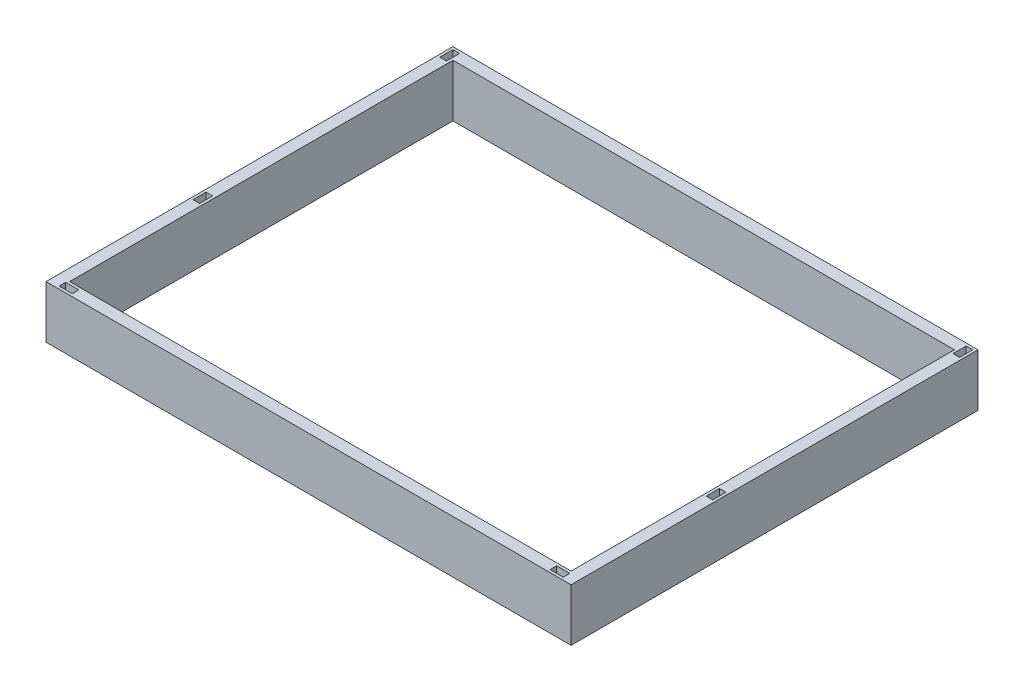
SolidWorks part; units mm, degrees
material "ABS"
ref_plane "Front Plane" through (0, 0, 0) normal (0, 0, 1) x (1, 0, 0)
ref_plane "Top Plane" through (0, 0, 0) normal (0, 1, 0) x (1, 0, 0)
ref_plane "Right Plane" through (0, 0, 0) normal (1, 0, 0) x (0, 0, -1)
sketch "Sketch1" plane through (0, 0, 0) normal (0, 1, 0) x (1, 0, 0)
  line L1 (100, 77.5) -> (-100, 77.5)
  line L2 (100, 77.5) -> (100, -77.5)
  line L3 (100, -77.5) -> (-100, -77.5)
  line L4 (-100, 77.5) -> (-100, -77.5)
  line L5 (100, 77.5) -> (-100, -77.5) construction
  line L6 (100, -77.5) -> (-100, 77.5) construction
  line L15 (95.5, 73) -> (-95.5, 73)
  line L16 (95.5, 73) -> (95.5, -73)
  line L21 (95.5, -73) -> (-95.5, -73)
  line L22 (-95.5, 73) -> (-95.5, -73)
  line L35 (96, -76.5) -> (91, -76.5)
  line L36 (96, -76.5) -> (96, -74)
  line L37 (96, -74) -> (91, -74)
  line L38 (91, -76.5) -> (91, -74)
  line L39 (96, -76.5) -> (91, -74) construction
  line L40 (96, -74) -> (91, -76.5) construction
  line L47 (-96, -76.5) -> (-91, -76.5)
  line L48 (-96, -76.5) -> (-96, -74)
  line L49 (-96, -74) -> (-91, -74)
  line L50 (-91, -76.5) -> (-91, -74)
  line L51 (-96, -76.5) -> (-91, -74) construction
  line L52 (-96, -74) -> (-91, -76.5) construction
  line L65 (99, -17.5) -> (96.5, -17.5)
  line L66 (99, -17.5) -> (99, -22.5)
  line L67 (99, -22.5) -> (96.5, -22.5)
  line L68 (96.5, -17.5) -> (96.5, -22.5)
  line L69 (99, -17.5) -> (96.5, -22.5) construction
  line L70 (99, -22.5) -> (96.5, -17.5) construction
  line L71 (99, 76.5) -> (96.5, 76.5)
  line L72 (99, 76.5) -> (99, 71.5)
  line L73 (99, 71.5) -> (96.5, 71.5)
  line L74 (96.5, 76.5) -> (96.5, 71.5)
  line L75 (99, 76.5) -> (96.5, 71.5) construction
  line L76 (99, 71.5) -> (96.5, 76.5) construction
  line L77 (-99, -17.5) -> (-96.5, -17.5)
  line L78 (-99, -17.5) -> (-99, -22.5)
  line L79 (-99, -22.5) -> (-96.5, -22.5)
  line L80 (-96.5, -17.5) -> (-96.5, -22.5)
  line L81 (-99, -17.5) -> (-96.5, -22.5) construction
  line L82 (-99, -22.5) -> (-96.5, -17.5) construction
  line L83 (-99, 71.5) -> (-96.5, 71.5)
  line L84 (-99, 71.5) -> (-99, 76.5)
  line L85 (-99, 76.5) -> (-96.5, 76.5)
  line L86 (-96.5, 71.5) -> (-96.5, 76.5)
  line L87 (-99, 71.5) -> (-96.5, 76.5) construction
  line L88 (-99, 76.5) -> (-96.5, 71.5) construction
  line L89 (95.5, 73) -> (-95.5, -73) construction
  line L90 (95.5, -73) -> (-95.5, 73) construction
  point P0 (0, 0)
  point P6 (0, 0)
  point P38 (93.5, -75.25)
  point P48 (-93.5, -75.25)
  point P59 (97.75, -20)
  point P68 (97.75, -17.5)
  point P69 (97.75, 74)
  point P74 (-97.75, -20)
  point P79 (-97.75, 74)
  dimension "D7" = 4.5
  dimension "D8" = 4.5
  dimension "D1" = 200
  dimension "D2" = 155
  dimension "D31" = 4
  dimension "D32" = 1
  dimension "D33" = 5
  dimension "D34" = 2.5
  dimension "D39" = 1
  dimension "D40" = 4
  dimension "D41" = 5
  dimension "D42" = 2.5
  dimension "D51" = 1
  dimension "D52" = 5
  dimension "D53" = 2.5
  dimension "D54" = 55
  dimension "D55" = 1
  dimension "D56" = 1
  dimension "D57" = 5
  dimension "D58" = 2.5
  dimension "D59" = 1
  dimension "D60" = 55
  dimension "D61" = 2.5
  dimension "D62" = 5
  dimension "D63" = 1
  dimension "D64" = 1
  dimension "D65" = 2.5
  dimension "D66" = 5
extrude "MainBody" add sketch "Sketch1" along normal blind 20
